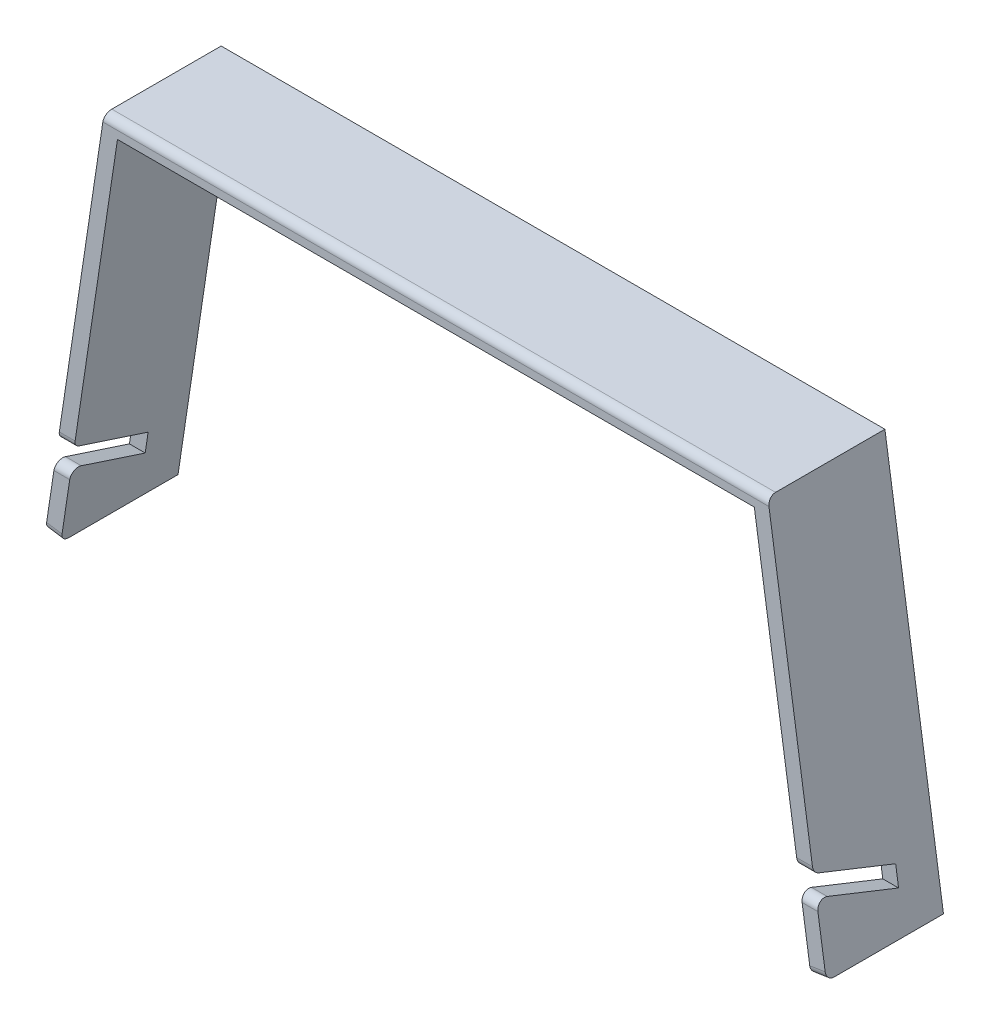
SolidWorks part; units mm, degrees
ref_plane "Ebene vorne" through (0, 0, 0) normal (0, 0, 1) x (1, 0, 0)
ref_plane "Ebene oben" through (0, 0, 0) normal (0, 1, 0) x (1, 0, 0)
ref_plane "Ebene rechts" through (0, 0, 0) normal (1, 0, 0) x (0, 0, -1)
sketch "Skizze1" plane through (0, 0, 0) normal (0, 0, 1) x (1, 0, 0)
  line L0 (-50, 0) -> (-42.5, 50)
  line L1 (-42.5, 50) -> (42.5, 50)
  line L2 (42.5, 50) -> (50, 0)
  line L3 (0, 50) -> (0, 0) construction
  line L4 (-50, 0) -> (50, 0) construction
  point P2 (0, 50)
  dimension "D1" = 50
  dimension "D2" = 7.5
  dimension "D3" = 85
  dimension "D4" = 100
extrude "Linear-Austragen-Dünn1" add sketch "Skizze1" along normal blind 15 thin
fillet "Verrundung1" radius 1 3 edges at (0, 50, 15) (49.0111, -0.1483, 15) (-49.0111, -0.1483, 15)
sketch "Skizze2" plane through (0, 0, 0) normal (1, 0, 0) x (0, 0, -1)
  line L0 (-15, 11.1397) -> (-5, 7.5)
  line L1 (-15, 49) -> (-15, 0.9889) construction
  line L2 (-5, 7.5) -> (-5, 5)
  line L3 (-5, 5) -> (-15, 8.6397)
  line L4 (-14, 0) -> (0, 0) construction
  line L5 (-15, 11.1397) -> (-15, 8.6397)
  dimension "D1" = 2.5
  dimension "D2" = 2.5
  dimension "D3" = 10
  dimension "D4" = 70
  dimension "D5" = 5
extrude "Schnitt-Linear austragen2" cut sketch "Skizze2" against normal through all both and the other way through all
fillet "Verrundung2" radius 1 4 edges at (-47.6929, 8.6397, 15) (-47.3179, 11.1397, 15) (47.6929, 8.6397, 15) (47.3179, 11.1397, 15)
